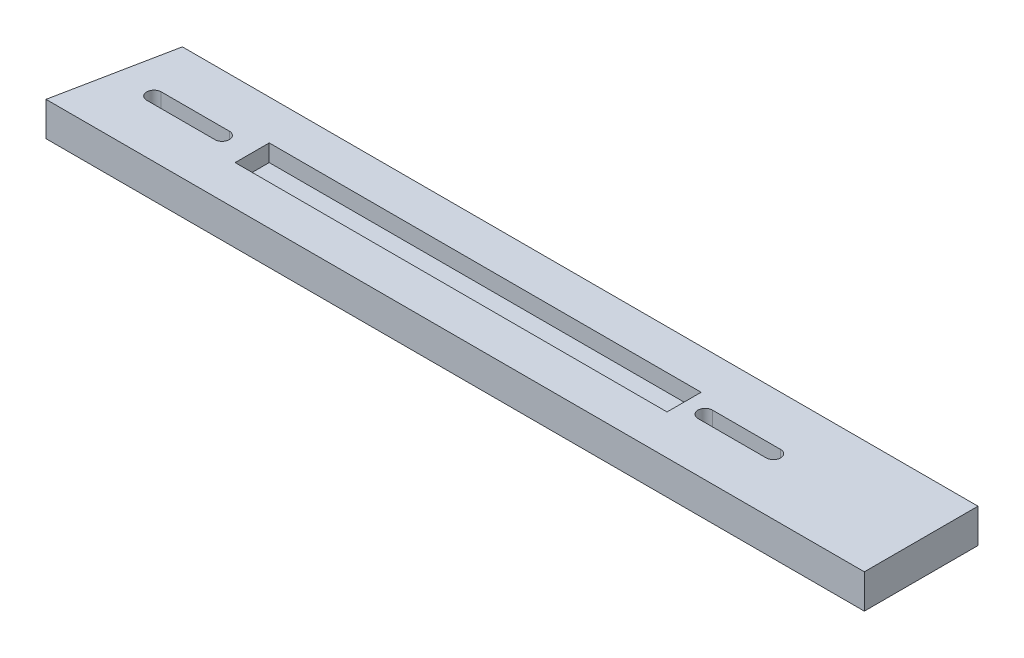
SolidWorks part; units mm, degrees
ref_plane "Front" through (0, 0, 0) normal (0, 0, 1) x (1, 0, 0)
ref_plane "Top" through (0, 0, 0) normal (0, 1, 0) x (1, 0, 0)
ref_plane "Right" through (0, 0, 0) normal (1, 0, 0) x (0, 0, -1)
sketch "Sketch1" plane through (0, 0, 0) normal (0, 1, 0) x (1, 0, 0)
  line L1 (228.6, -31.75) -> (-228.6, -31.75)
  line L2 (228.6, -31.75) -> (228.6, 31.75)
  line L3 (228.6, 31.75) -> (-228.6, 31.75)
  line L4 (-228.6, -31.75) -> (-228.6, 31.75)
  line L5 (228.6, -31.75) -> (-228.6, 31.75) construction
  line L6 (228.6, 31.75) -> (-228.6, -31.75) construction
  point P0 (0, 0)
  dimension "D1" = 63.5
  dimension "D2" = 457.2
extrude "Boss-Extrude1" add sketch "Sketch1" along normal blind 19.05
sketch "Sketch2" plane through (0, 19.05, 0) normal (0, 1, 0) x (1, 0, 0)
  line L0 (146.05, 0) -> (107.95, 0) construction
  line L1 (146.05, -4.064) -> (107.95, -4.064)
  line L2 (146.05, 4.064) -> (107.95, 4.064)
  line L4 (0, 0) -> (-180.975, 0) construction
  line L6 (-200.025, 0) -> (-161.925, 0) construction
  line L7 (-200.025, 4.064) -> (-161.925, 4.064)
  line L8 (-200.025, -4.064) -> (-161.925, -4.064)
  line L10 (0, 0) -> (127, 0) construction
  line L11 (-228.6, 31.75) -> (-228.6, -31.75) construction
  line L12 (228.6, -31.75) -> (228.6, 31.75) construction
  arc A0 (146.05, -4.064) -> (146.05, 4.064) centre (146.05, 0) ccw
  arc A1 (107.95, 4.064) -> (107.95, -4.064) centre (107.95, 0) ccw
  arc A2 (-200.025, 4.064) -> (-200.025, -4.064) centre (-200.025, 0) ccw
  arc A3 (-161.925, -4.064) -> (-161.925, 4.064) centre (-161.925, 0) ccw
  point P2 (127, 0)
  point P17 (-180.975, 0)
  dimension "D4" = 8.128
  dimension "D1" = 8.128
  dimension "D2" = 38.1
  dimension "D3" = 28.575
  dimension "D5" = 82.55
  dimension "D6" = 38.1
extrude "Cut-Extrude1" cut sketch "Sketch2" against normal blind 19.05
sketch "Sketch3" plane through (0, 19.05, 0) normal (0, 1, 0) x (1, 0, 0)
  line L0 (-228.6, 31.75) -> (-228.6, -31.75)
  line L1 (-228.6, -31.75) -> (228.6, -31.75) construction
  line L2 (-228.6, 31.75) -> (-228.6, -31.75) construction
  line L4 (-228.6, -31.75) -> (-215.9, 31.75)
  line L5 (228.6, 31.75) -> (-228.6, 31.75) construction
  line L6 (-215.9, 31.75) -> (-228.6, 31.75)
  line L7 (0, 0) -> (0, 31.75) construction
  dimension "D1" = 12.7
extrude "Cut-Extrude2" cut sketch "Sketch3" against normal through all
sketch "Sketch4" plane through (0, 19.05, 0) normal (0, 1, 0) x (1, 0, 0)
  line L0 (0, 0) -> (168.275, 0) construction
  circle A0 centre (168.275, 0) radius 4.0005
  arc A1 (-200.025, 4.064) -> (-200.025, -4.064) centre (-200.025, 0) ccw construction
  dimension "D1" = 8.001
  dimension "D2" = 368.3
extrude "Boss-Extrude2" [suppressed] add sketch "Sketch4" along normal blind 25.4
sketch "Sketch5" plane through (0, 19.05, 0) normal (0, 1, 0) x (1, 0, 0)
  line L0 (-65.8909, 31.75) -> (-65.8909, 9.525) construction
  line L1 (-145.161, 9.525) -> (96.139, 9.525)
  line L2 (-145.161, 9.525) -> (-145.161, -9.525)
  line L3 (-145.161, -9.525) -> (96.139, -9.525)
  line L4 (96.139, 9.525) -> (96.139, -9.525)
  line L5 (228.6, 31.75) -> (-215.9, 31.75) construction
  line L6 (-65.8909, 9.525) -> (-65.8909, -9.525) construction
  line L7 (-65.8909, -9.525) -> (-65.8909, -31.75) construction
  line L8 (-228.6, -31.75) -> (228.6, -31.75) construction
  arc A0 (-161.925, -4.064) -> (-161.925, 4.064) centre (-161.925, 0) ccw construction
  point P8 (-157.861, 0)
  dimension "D1" = 19.05
  dimension "D2" = 241.3
  dimension "D3" = 12.7
extrude "Cut-Extrude3" cut sketch "Sketch5" against normal blind 9.525
